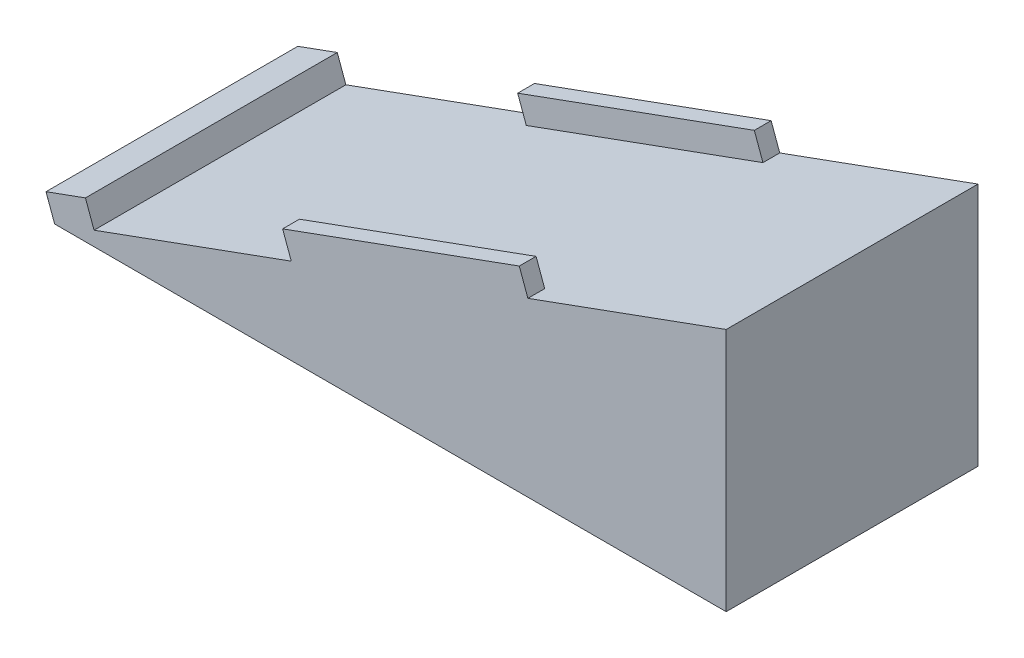
SolidWorks part; units mm, degrees
ref_plane "Front" through (0, 0, 0) normal (0, 0, 1) x (1, 0, 0)
ref_plane "Top" through (0, 0, 0) normal (0, 1, 0) x (1, 0, 0)
ref_plane "Right" through (0, 0, 0) normal (1, 0, 0) x (0, 0, -1)
sketch "Sketch1" plane through (0, 0, 0) normal (0, 0, 1) x (1, 0, 0)
  line L0 (0, 0) -> (80, 0)
  line L1 (0, 0) -> (80, 29.1176)
  line L2 (80, 29.1176) -> (80, 0)
  dimension "D1" = 80
  dimension "D2" = 20
extrude "Boss-Extrude1" add sketch "Sketch1" along normal blind 30
sketch "Sketch2" plane through (0, 0, 0) normal (-0.342, 0.9397, 0) x (0.9397, 0.342, 0)
  line L0 (85.1342, -30) -> (0, -30) construction
  line L1 (0, 0) -> (5, 0)
  line L2 (0, 0) -> (0, -30)
  line L3 (0, -30) -> (5, -30)
  line L4 (5, 0) -> (5, -30)
  line L5 (85.1342, 0) -> (0, 0) construction
  line L7 (30, 0) -> (60, 0)
  line L8 (30, 0) -> (30, -2)
  line L9 (30, -2) -> (60, -2)
  line L10 (60, 0) -> (60, -2)
  line L11 (30, -30) -> (60, -30)
  line L12 (30, -30) -> (30, -28)
  line L13 (30, -28) -> (60, -28)
  line L14 (60, -30) -> (60, -28)
  dimension "D1" = 5
  dimension "D2" = 2
  dimension "D3" = 30
  dimension "D4" = 25
  dimension "D5" = 2
  dimension "D6" = 30
extrude "Boss-Extrude2" add sketch "Sketch2" along normal blind 3
